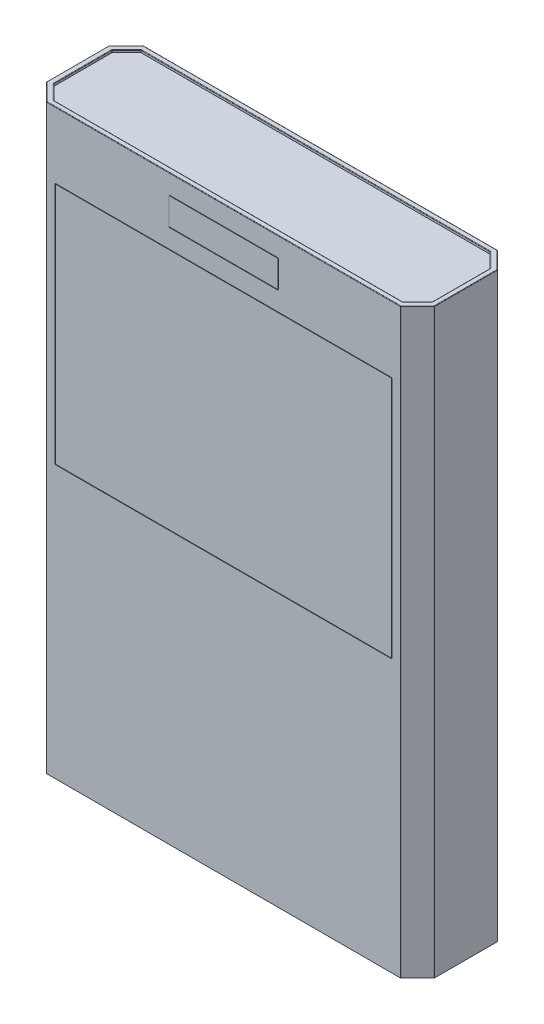
SolidWorks part; units mm, degrees
ref_plane "Front Plane" through (0, 0, 0) normal (0, 0, 1) x (1, 0, 0)
ref_plane "Top Plane" through (0, 0, 0) normal (0, 1, 0) x (1, 0, 0)
ref_plane "Right Plane" through (0, 0, 0) normal (1, 0, 0) x (0, 0, -1)
sketch "Sketch2" plane through (0, 0, 0) normal (0, 0, 1) x (1, 0, 0)
  line L1 (-40, -60) -> (40, -60)
  line L2 (-40, -60) -> (-40, 60)
  line L3 (-40, 60) -> (40, 60)
  line L4 (40, -60) -> (40, 60)
  line L5 (-40, -60) -> (40, 60) construction
  line L6 (-40, 60) -> (40, -60) construction
  point P0 (0, 0)
  dimension "D1" = 80
  dimension "D2" = 120
extrude "Boss-Extrude1" add sketch "Sketch2" along normal blind 20
chamfer "Chamfer1" distance 3.5 angle 45 4 edges at (-40, 0, 0) (-40, 0, 20) (40, 0, 20) (40, 0, 0)
sketch "Sketch3" plane through (0, 60, 0) normal (0, 1, 0) x (1, 0, 0)
  line L0 (36.5, 0) -> (-36.5, 0) construction
  line L1 (-36, -19) -> (36, -19)
  line L2 (-39, -16) -> (-39, -4)
  line L3 (-36, -1) -> (36, -1)
  line L4 (39, -16) -> (39, -4)
  line L5 (-39, -19) -> (39, -1) construction
  line L6 (-39, -1) -> (39, -19) construction
  line L7 (36, -1) -> (39, -4)
  line L8 (36.5, -20) -> (-36.5, -20) construction
  line L9 (40, -16.5) -> (40, -3.5) construction
  line L10 (-40, -16.5) -> (-40, -3.5) construction
  line L11 (36, -19) -> (39, -16)
  line L12 (-39, -16) -> (-36, -19)
  line L13 (-39, -4) -> (-36, -1)
  point P0 (0, -10)
  dimension "D1" = 1
  dimension "D2" = 1
  dimension "D3" = 1
  dimension "D4" = 1
extrude "Cut-Extrude1" cut sketch "Sketch3" against normal blind 0.5 contours L3 L7 L4 L11 L1 L12 L2 L13
fillet "Fillet1" radius 0.1 31 edges at (-36, 59.75, 19) (-39, 59.75, 16) (-39, 59.75, 4) (-36, 59.75, 1) (36, 59.75, 19) (39, 59.75, 16) (39, 59.75, 4) (36, 59.75, 1) (-40, 0, 16.5) (-36.5, 0, 20) (-38.25, 60, 18.25) (-40, 0, 3.5) (-38.25, 60, 1.75) (-36.5, 0, 0) (0, 60, 0) (36.5, 0, 0) (38.25, 60, 1.75) (40, 0, 3.5) (40, 60, 10) (40, 0, 16.5) (38.25, 60, 18.25) (0, 60, 20) (36.5, 0, 20) (37.5, 60, 2.5) (39, 60, 10) (37.5, 60, 17.5) (0, 60, 19) (-37.5, 60, 17.5) (-39, 60, 10) (-37.5, 60, 2.5) (0, 60, 1)
sketch "Sketch4" plane through (0, 0, 20) normal (0, 0, 1) x (1, 0, 0)
  line L0 (36.4586, 59.9) -> (-36.4586, 59.9) construction
  line L1 (-11.192, 50.308) -> (11.192, 50.308)
  line L2 (-11.192, 50.308) -> (-11.192, 55.892)
  line L3 (-11.192, 55.892) -> (11.192, 55.892)
  line L4 (11.192, 50.308) -> (11.192, 55.892)
  line L5 (-11.192, 50.308) -> (11.192, 55.892) construction
  line L6 (-11.192, 55.892) -> (11.192, 50.308) construction
  line L7 (-11.192, 50.208) -> (11.192, 50.208)
  line L8 (-11.292, 50.308) -> (-11.292, 55.892)
  line L9 (-11.192, 55.992) -> (11.192, 55.992)
  line L10 (11.292, 50.308) -> (11.292, 55.892)
  line L11 (-11.292, 50.208) -> (11.292, 55.992) construction
  line L12 (-11.292, 55.992) -> (11.292, 50.208) construction
  arc A0 (11.192, 55.992) -> (11.292, 55.892) centre (11.192, 55.892) cw
  arc A1 (11.192, 50.208) -> (11.292, 50.308) centre (11.192, 50.308) ccw
  arc A2 (-11.192, 50.208) -> (-11.292, 50.308) centre (-11.192, 50.308) cw
  arc A3 (-11.292, 55.892) -> (-11.192, 55.992) centre (-11.192, 55.892) cw
  point P0 (0, 53.1)
  point P5 (0, 53.1)
  dimension "D6" = 0.1
  dimension "D1" = 22.384
  dimension "D2" = 0
  dimension "D3" = 5.584
  dimension "D4" = 0.1
  dimension "D5" = 0.1
  dimension "D7" = 6.8
extrude "Cut-Extrude2" cut sketch "Sketch4" against normal blind 0.1
sketch "Sketch6" plane through (0, 0, 20) normal (0, 0, 1) x (1, 0, 0)
  line L0 (-11.192, 50.208) -> (11.192, 50.208) construction
  line L1 (-34.61, -3.802) -> (34.61, -3.802)
  line L2 (-34.61, -3.802) -> (-34.61, 46.218)
  line L3 (-34.61, 46.218) -> (34.61, 46.218)
  line L4 (34.61, -3.802) -> (34.61, 46.218)
  line L5 (-34.61, -3.802) -> (34.61, 46.218) construction
  line L6 (-34.61, 46.218) -> (34.61, -3.802) construction
  line L7 (-34.61, -3.902) -> (34.61, -3.902)
  line L8 (-34.71, -3.802) -> (-34.71, 46.218)
  line L9 (-34.61, 46.318) -> (34.61, 46.318)
  line L10 (34.71, -3.802) -> (34.71, 46.218)
  line L11 (-34.71, -3.902) -> (34.71, 46.318) construction
  line L12 (-34.71, 46.318) -> (34.71, -3.902) construction
  arc A0 (-34.61, -3.902) -> (-34.71, -3.802) centre (-34.61, -3.802) cw
  arc A1 (34.61, -3.902) -> (34.71, -3.802) centre (34.61, -3.802) ccw
  arc A2 (34.61, 46.318) -> (34.71, 46.218) centre (34.61, 46.218) cw
  arc A3 (-34.71, 46.218) -> (-34.61, 46.318) centre (-34.61, 46.218) cw
  point P0 (0, 21.208)
  point P5 (0, 21.208)
  dimension "D6" = 0.1
  dimension "D1" = 69.22
  dimension "D2" = 0
  dimension "D3" = 50.02
  dimension "D4" = 0.1
  dimension "D5" = 0.1
  dimension "D7" = 29
extrude "Cut-Extrude4" cut sketch "Sketch6" against normal blind 0.1 contours A3 L8 A0 L7 A1 L10 A2 L9 L4 L1 L2 L3
sketch "Sketch7" plane through (0, 0, 20) normal (0, 0, 1) x (1, 0, 0)
  line L10 (6.79, -32.502) -> (28.79, -32.502)
  line L11 (6.79, -32.502) -> (6.79, -22.902)
  line L12 (6.79, -22.902) -> (28.79, -22.902)
  line L13 (28.79, -32.502) -> (28.79, -22.902)
  line L14 (6.79, -32.502) -> (28.79, -22.902) construction
  line L19 (6.79, -22.902) -> (28.79, -32.502) construction
  line L20 (6.79, -45.902) -> (28.79, -45.902)
  line L22 (6.79, -45.902) -> (6.79, -36.302)
  line L23 (6.79, -36.302) -> (28.79, -36.302)
  line L24 (28.79, -45.902) -> (28.79, -36.302)
  line L25 (6.79, -45.902) -> (28.79, -36.302) construction
  line L26 (6.79, -36.302) -> (28.79, -45.902) construction
  dimension "D5" = 22
  dimension "D7" = 22
  dimension "D8" = 13.4
  dimension "D9" = 9.6
  dimension "D10" = 9.6
